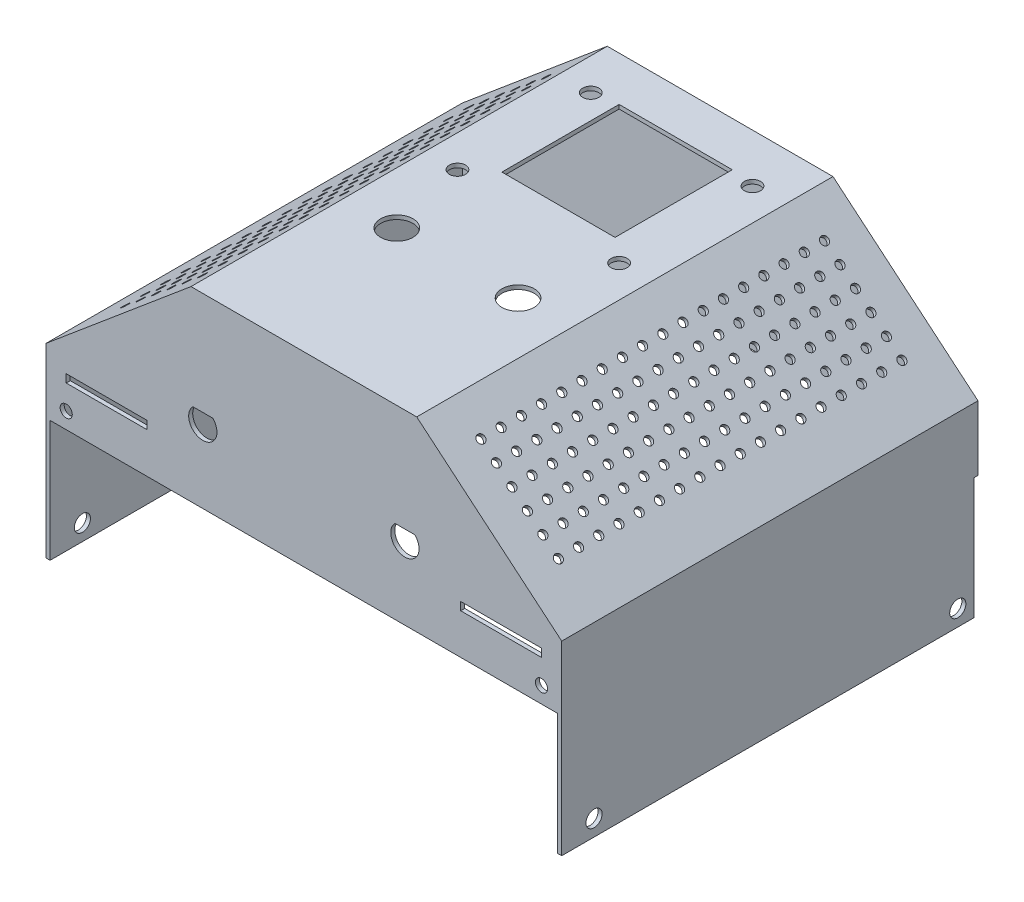
SolidWorks part; units mm, degrees
ref_plane "前视基准面" through (0, 0, 0) normal (0, 0, 1) x (1, 0, 0)
ref_plane "上视基准面" through (0, 0, 0) normal (0, 1, 0) x (1, 0, 0)
ref_plane "右视基准面" through (0, 0, 0) normal (1, 0, 0) x (0, 0, -1)
sketch "草图1" plane through (0, 0, 0) normal (0, 0, 1) x (1, 0, 0)
  line L0 (0, 0) -> (0, 61.6367) construction
  line L1 (0, 76.1019) -> (27.9259, 76.1019)
  line L2 (27.9259, 76.1019) -> (63.8, 46)
  line L3 (63.8, 46) -> (63.8, 0)
  line L4 (0, 75.1019) -> (27.562, 75.1019)
  line L5 (27.562, 75.1019) -> (62.8, 45.5337)
  line L6 (62.8, 45.5337) -> (62.8, 0)
  line L7 (63.8, 0) -> (62.8, 0)
  line L8 (-63.8, 0) -> (-62.8, 0)
  line L9 (-62.8, 45.5337) -> (-62.8, 0)
  line L10 (-27.562, 75.1019) -> (-62.8, 45.5337)
  line L11 (0, 75.1019) -> (-27.562, 75.1019)
  line L12 (-63.8, 46) -> (-63.8, 0)
  line L13 (-27.9259, 76.1019) -> (-63.8, 46)
  line L14 (0, 76.1019) -> (-27.9259, 76.1019)
  dimension "D2" = 125.6
  dimension "D3" = 46
  dimension "D4" = 130
  dimension "D5" = 46
  dimension "D1" = 1
extrude "凸台-拉伸1" add sketch "草图1" along normal blind 102
sketch "草图2" plane through (0, 76.1019, 0) normal (0, 1, 0) x (1, 0, 0)
  line L0 (-28.1681, -27.5) -> (23.8319, -27.5) construction
  line L1 (14, -10) -> (-14, -10)
  line L2 (-14, -10) -> (-14, -39)
  line L3 (-14, -39) -> (14, -39)
  line L4 (14, -10) -> (14, -39)
  line L5 (0, -39) -> (0, -44) construction
  line L6 (20, -44) -> (20, -35.7431) construction
  line L7 (-20, -44) -> (-20, -39.6804) construction
  line L8 (-20, -44) -> (20, -44) construction
  line L9 (-20, -11) -> (20, -11) construction
  line L10 (0, -39) -> (0, 0) construction
  line L11 (27.9259, 0) -> (-27.9259, 0) construction
  circle A0 centre (-20, -11) radius 2
  circle A1 centre (20, -11) radius 2
  circle A2 centre (20, -44) radius 2
  circle A3 centre (-20, -44) radius 2
  circle A4 centre (15, -64) radius 4
  circle A5 centre (-15, -64) radius 4
  point P14 (0, -39)
  point P15 (0, -10)
  dimension "D5" = 40
  dimension "D6" = 4
  dimension "D7" = 4
  dimension "D9" = 8
  dimension "D10" = 30
  dimension "D1" = 33
  dimension "D2" = 29
  dimension "D3" = 28
  dimension "D4" = 1
  dimension "D8" = 10
  dimension "D11" = 20
extrude "切除-拉伸1" cut sketch "草图2" against normal up to next
sketch "草图3" plane through (-49.0112, 58.4093, 0) normal (-0.6428, 0.766, 0) x (0.766, 0.6428, 0)
  line L0 (27.5249, 0) -> (-19.3054, 0) construction
  line L1 (27.5249, -102) -> (27.5249, 0) construction
  circle A0 centre (19.5249, -8) radius 1
  circle A1 centre (14.5249, -8) radius 1
  circle A2 centre (9.5249, -8) radius 1
  circle A3 centre (4.5249, -8) radius 1
  circle A4 centre (-0.4751, -8) radius 1
  circle A5 centre (-5.4751, -8) radius 1
  circle A6 centre (14.5249, -13) radius 1
  circle A7 centre (9.5249, -13) radius 1
  circle A8 centre (4.5249, -13) radius 1
  circle A9 centre (-0.4751, -13) radius 1
  circle A10 centre (-5.4751, -13) radius 1
  circle A11 centre (14.5249, -18) radius 1
  circle A12 centre (9.5249, -18) radius 1
  circle A13 centre (4.5249, -18) radius 1
  circle A14 centre (-0.4751, -18) radius 1
  circle A15 centre (-5.4751, -18) radius 1
  circle A16 centre (14.5249, -23) radius 1
  circle A17 centre (9.5249, -23) radius 1
  circle A18 centre (4.5249, -23) radius 1
  circle A19 centre (-0.4751, -23) radius 1
  circle A20 centre (-5.4751, -23) radius 1
  circle A21 centre (14.5249, -28) radius 1
  circle A22 centre (9.5249, -28) radius 1
  circle A23 centre (4.5249, -28) radius 1
  circle A24 centre (-0.4751, -28) radius 1
  circle A25 centre (-5.4751, -28) radius 1
  circle A26 centre (14.5249, -33) radius 1
  circle A27 centre (9.5249, -33) radius 1
  circle A28 centre (4.5249, -33) radius 1
  circle A29 centre (-0.4751, -33) radius 1
  circle A30 centre (-5.4751, -33) radius 1
  circle A31 centre (14.5249, -38) radius 1
  circle A32 centre (9.5249, -38) radius 1
  circle A33 centre (4.5249, -38) radius 1
  circle A34 centre (-0.4751, -38) radius 1
  circle A35 centre (-5.4751, -38) radius 1
  circle A36 centre (14.5249, -43) radius 1
  circle A37 centre (9.5249, -43) radius 1
  circle A38 centre (4.5249, -43) radius 1
  circle A39 centre (-0.4751, -43) radius 1
  circle A40 centre (-5.4751, -43) radius 1
  circle A41 centre (14.5249, -48) radius 1
  circle A42 centre (9.5249, -48) radius 1
  circle A43 centre (4.5249, -48) radius 1
  circle A44 centre (-0.4751, -48) radius 1
  circle A45 centre (-5.4751, -48) radius 1
  circle A46 centre (14.5249, -53) radius 1
  circle A47 centre (9.5249, -53) radius 1
  circle A48 centre (4.5249, -53) radius 1
  circle A49 centre (-0.4751, -53) radius 1
  circle A50 centre (-5.4751, -53) radius 1
  circle A51 centre (14.5249, -58) radius 1
  circle A52 centre (9.5249, -58) radius 1
  circle A53 centre (4.5249, -58) radius 1
  circle A54 centre (-0.4751, -58) radius 1
  circle A55 centre (-5.4751, -58) radius 1
  circle A56 centre (14.5249, -63) radius 1
  circle A57 centre (9.5249, -63) radius 1
  circle A58 centre (4.5249, -63) radius 1
  circle A59 centre (-0.4751, -63) radius 1
  circle A60 centre (-5.4751, -63) radius 1
  circle A61 centre (14.5249, -68) radius 1
  circle A62 centre (9.5249, -68) radius 1
  circle A63 centre (4.5249, -68) radius 1
  circle A64 centre (-0.4751, -68) radius 1
  circle A65 centre (-5.4751, -68) radius 1
  circle A66 centre (14.5249, -73) radius 1
  circle A67 centre (9.5249, -73) radius 1
  circle A68 centre (4.5249, -73) radius 1
  circle A69 centre (-0.4751, -73) radius 1
  circle A70 centre (-5.4751, -73) radius 1
  circle A71 centre (14.5249, -78) radius 1
  circle A72 centre (9.5249, -78) radius 1
  circle A73 centre (4.5249, -78) radius 1
  circle A74 centre (-0.4751, -78) radius 1
  circle A75 centre (-5.4751, -78) radius 1
  circle A76 centre (14.5249, -83) radius 1
  circle A77 centre (9.5249, -83) radius 1
  circle A78 centre (4.5249, -83) radius 1
  circle A79 centre (-0.4751, -83) radius 1
  circle A80 centre (-5.4751, -83) radius 1
  circle A81 centre (14.5249, -88) radius 1
  circle A82 centre (9.5249, -88) radius 1
  circle A83 centre (4.5249, -88) radius 1
  circle A84 centre (-0.4751, -88) radius 1
  circle A85 centre (-5.4751, -88) radius 1
  circle A86 centre (14.5249, -93) radius 1
  circle A87 centre (9.5249, -93) radius 1
  circle A88 centre (4.5249, -93) radius 1
  circle A89 centre (-0.4751, -93) radius 1
  circle A90 centre (-5.4751, -93) radius 1
  circle A91 centre (19.5249, -13) radius 1
  circle A92 centre (19.5249, -18) radius 1
  circle A93 centre (19.5249, -23) radius 1
  circle A94 centre (19.5249, -28) radius 1
  circle A95 centre (19.5249, -33) radius 1
  circle A96 centre (19.5249, -38) radius 1
  circle A97 centre (19.5249, -43) radius 1
  circle A98 centre (19.5249, -48) radius 1
  circle A99 centre (19.5249, -53) radius 1
  circle A100 centre (19.5249, -58) radius 1
  circle A101 centre (19.5249, -63) radius 1
  circle A102 centre (19.5249, -68) radius 1
  circle A103 centre (19.5249, -73) radius 1
  circle A104 centre (19.5249, -78) radius 1
  circle A105 centre (19.5249, -83) radius 1
  circle A106 centre (19.5249, -88) radius 1
  circle A107 centre (19.5249, -93) radius 1
  dimension "D1" = 2
  dimension "D4" = 8
  dimension "D5" = 8
  dimension "D2" = 6
  dimension "D3" = 18
extrude "切除-拉伸2" cut sketch "草图3" against normal up to next (1 mm away)
sketch "草图4" plane through (49.0112, 58.4093, 0) normal (0.6428, 0.766, 0) x (0.766, -0.6428, 0)
  line L0 (-27.5249, -102) -> (-27.5249, 0) construction
  line L1 (19.3054, 0) -> (-27.5249, 0) construction
  circle A0 centre (-18.5249, -8) radius 1
  circle A1 centre (-13.5249, -8) radius 1
  circle A2 centre (-8.5249, -8) radius 1
  circle A3 centre (-3.5249, -8) radius 1
  circle A4 centre (1.4751, -8) radius 1
  circle A5 centre (6.4751, -8) radius 1
  circle A6 centre (-13.5249, -13) radius 1
  circle A7 centre (-8.5249, -13) radius 1
  circle A8 centre (-3.5249, -13) radius 1
  circle A9 centre (1.4751, -13) radius 1
  circle A10 centre (6.4751, -13) radius 1
  circle A11 centre (-13.5249, -18) radius 1
  circle A12 centre (-8.5249, -18) radius 1
  circle A13 centre (-3.5249, -18) radius 1
  circle A14 centre (1.4751, -18) radius 1
  circle A15 centre (6.4751, -18) radius 1
  circle A16 centre (-13.5249, -23) radius 1
  circle A17 centre (-8.5249, -23) radius 1
  circle A18 centre (-3.5249, -23) radius 1
  circle A19 centre (1.4751, -23) radius 1
  circle A20 centre (6.4751, -23) radius 1
  circle A21 centre (-13.5249, -28) radius 1
  circle A22 centre (-8.5249, -28) radius 1
  circle A23 centre (-3.5249, -28) radius 1
  circle A24 centre (1.4751, -28) radius 1
  circle A25 centre (6.4751, -28) radius 1
  circle A26 centre (-13.5249, -33) radius 1
  circle A27 centre (-8.5249, -33) radius 1
  circle A28 centre (-3.5249, -33) radius 1
  circle A29 centre (1.4751, -33) radius 1
  circle A30 centre (6.4751, -33) radius 1
  circle A31 centre (-13.5249, -38) radius 1
  circle A32 centre (-8.5249, -38) radius 1
  circle A33 centre (-3.5249, -38) radius 1
  circle A34 centre (1.4751, -38) radius 1
  circle A35 centre (6.4751, -38) radius 1
  circle A36 centre (-13.5249, -43) radius 1
  circle A37 centre (-8.5249, -43) radius 1
  circle A38 centre (-3.5249, -43) radius 1
  circle A39 centre (1.4751, -43) radius 1
  circle A40 centre (6.4751, -43) radius 1
  circle A41 centre (-13.5249, -48) radius 1
  circle A42 centre (-8.5249, -48) radius 1
  circle A43 centre (-3.5249, -48) radius 1
  circle A44 centre (1.4751, -48) radius 1
  circle A45 centre (6.4751, -48) radius 1
  circle A46 centre (-13.5249, -53) radius 1
  circle A47 centre (-8.5249, -53) radius 1
  circle A48 centre (-3.5249, -53) radius 1
  circle A49 centre (1.4751, -53) radius 1
  circle A50 centre (6.4751, -53) radius 1
  circle A51 centre (-13.5249, -58) radius 1
  circle A52 centre (-8.5249, -58) radius 1
  circle A53 centre (-3.5249, -58) radius 1
  circle A54 centre (1.4751, -58) radius 1
  circle A55 centre (6.4751, -58) radius 1
  circle A56 centre (-13.5249, -63) radius 1
  circle A57 centre (-8.5249, -63) radius 1
  circle A58 centre (-3.5249, -63) radius 1
  circle A59 centre (1.4751, -63) radius 1
  circle A60 centre (6.4751, -63) radius 1
  circle A61 centre (-13.5249, -68) radius 1
  circle A62 centre (-8.5249, -68) radius 1
  circle A63 centre (-3.5249, -68) radius 1
  circle A64 centre (1.4751, -68) radius 1
  circle A65 centre (6.4751, -68) radius 1
  circle A66 centre (-13.5249, -73) radius 1
  circle A67 centre (-8.5249, -73) radius 1
  circle A68 centre (-3.5249, -73) radius 1
  circle A69 centre (1.4751, -73) radius 1
  circle A70 centre (6.4751, -73) radius 1
  circle A71 centre (-13.5249, -78) radius 1
  circle A72 centre (-8.5249, -78) radius 1
  circle A73 centre (-3.5249, -78) radius 1
  circle A74 centre (1.4751, -78) radius 1
  circle A75 centre (6.4751, -78) radius 1
  circle A76 centre (-13.5249, -83) radius 1
  circle A77 centre (-8.5249, -83) radius 1
  circle A78 centre (-3.5249, -83) radius 1
  circle A79 centre (1.4751, -83) radius 1
  circle A80 centre (6.4751, -83) radius 1
  circle A81 centre (-13.5249, -88) radius 1
  circle A82 centre (-8.5249, -88) radius 1
  circle A83 centre (-3.5249, -88) radius 1
  circle A84 centre (1.4751, -88) radius 1
  circle A85 centre (6.4751, -88) radius 1
  circle A86 centre (-13.5249, -93) radius 1
  circle A87 centre (-8.5249, -93) radius 1
  circle A88 centre (-3.5249, -93) radius 1
  circle A89 centre (1.4751, -93) radius 1
  circle A90 centre (6.4751, -93) radius 1
  circle A91 centre (-18.5249, -13) radius 1
  circle A92 centre (-18.5249, -18) radius 1
  circle A93 centre (-18.5249, -23) radius 1
  circle A94 centre (-18.5249, -28) radius 1
  circle A95 centre (-18.5249, -33) radius 1
  circle A96 centre (-18.5249, -38) radius 1
  circle A97 centre (-18.5249, -43) radius 1
  circle A98 centre (-18.5249, -48) radius 1
  circle A99 centre (-18.5249, -53) radius 1
  circle A100 centre (-18.5249, -58) radius 1
  circle A101 centre (-18.5249, -63) radius 1
  circle A102 centre (-18.5249, -68) radius 1
  circle A103 centre (-18.5249, -73) radius 1
  circle A104 centre (-18.5249, -78) radius 1
  circle A105 centre (-18.5249, -83) radius 1
  circle A106 centre (-18.5249, -88) radius 1
  circle A107 centre (-18.5249, -93) radius 1
  dimension "D1" = 2
  dimension "D2" = 9
  dimension "D3" = 8
  dimension "D4" = 6
  dimension "D5" = 18
extrude "切除-拉伸3" cut sketch "草图4" against normal up to next (1 mm away)
sketch "草图5" plane through (0, 0, 0) normal (0, 0, -1) x (-1, 0, 0)
  line L0 (63.8, 46) -> (63.8, 0) construction
  line L1 (-63.8, 0) -> (-63.8, 46) construction
  line L2 (27.9259, 76.1019) -> (63.8, 46) construction
  line L3 (-63.8, 46) -> (-27.9259, 76.1019) construction
  line L4 (-27.9259, 76.1019) -> (27.9259, 76.1019) construction
  line L5 (63.8, 46) -> (63.8, 30)
  line L6 (-63.8, 30) -> (-63.8, 46)
  line L7 (27.9259, 76.1019) -> (63.8, 46)
  line L8 (-63.8, 46) -> (-27.9259, 76.1019)
  line L9 (-27.9259, 76.1019) -> (27.9259, 76.1019)
  line L10 (-63.8, 30) -> (63.8, 30)
  line L11 (-62.8, 0) -> (-63.8, 0) construction
  dimension "D1" = 30
extrude "凸台-拉伸2" add sketch "草图5" along normal blind 1
sketch "草图6" plane through (63.8, 0, 0) normal (1, 0, 0) x (0, 0, -1)
  line L0 (3.3545, 4) -> (-111.4174, 4) construction
  line L1 (0, 0) -> (0, 30) construction
  line L2 (-102, 0) -> (0, 0) construction
  circle A0 centre (-4, 4) radius 2
  circle A1 centre (-94, 4) radius 2
  dimension "D1" = 4
  dimension "D2" = 4
  dimension "D3" = 90
  dimension "D4" = 4
  dimension "D5" = 4
extrude "切除-拉伸4" cut sketch "草图6" against normal through all
sketch "草图7" plane through (0, 0, 102) normal (0, 0, 1) x (1, 0, 0)
  line L0 (0, 30) -> (0, 85.8811) construction
  line L1 (22.5505, 50.6019) -> (27.4495, 50.6019)
  line L2 (-22.5505, 50.6019) -> (-27.4495, 50.6019)
  line L3 (38.8, 42) -> (38.8, 40)
  line L4 (-58.8, 42) -> (-38.8, 42)
  line L5 (-58.8, 42) -> (-58.8, 40)
  line L6 (-27.9259, 76.1019) -> (-63.8, 46)
  line L7 (27.9259, 76.1019) -> (-27.9259, 76.1019)
  line L8 (63.8, 46) -> (27.9259, 76.1019)
  line L9 (63.8, 30) -> (63.8, 46)
  line L10 (-63.8, 30) -> (63.8, 30)
  line L11 (-63.8, 46) -> (-63.8, 30)
  line L12 (-27.9259, 76.1019) -> (-63.8, 46)
  line L13 (27.9259, 76.1019) -> (-27.9259, 76.1019)
  line L14 (63.8, 46) -> (27.9259, 76.1019)
  line L15 (63.8, 30) -> (63.8, 46)
  line L16 (-63.8, 30) -> (63.8, 30)
  line L17 (-63.8, 46) -> (-63.8, 30)
  line L18 (-58.8, 40) -> (-38.8, 40)
  line L19 (-38.8, 42) -> (-38.8, 40)
  line L20 (58.8, 40) -> (38.8, 40)
  line L21 (58.8, 42) -> (58.8, 40)
  line L22 (58.8, 42) -> (38.8, 42)
  arc A0 (22.5505, 50.6019) -> (27.4495, 50.6019) centre (25, 48.1019) ccw
  arc A1 (-22.5505, 50.6019) -> (-27.4495, 50.6019) centre (-25, 48.1019) cw
  circle A2 centre (58.8, 34) radius 1.5
  circle A3 centre (-58.8, 34) radius 1.5
  dimension "D2" = 3.5
  dimension "D4" = 50
  dimension "D6" = 3
  dimension "D3" = 2.5
  dimension "D5" = 28
  dimension "D7" = 4
  dimension "D8" = 5
  dimension "D9" = 20
  dimension "D10" = 2
  dimension "D11" = 10
  dimension "D12" = 5
  dimension "D1" = 0
extrude "凸台-拉伸3" add sketch "草图7" against normal blind 1
